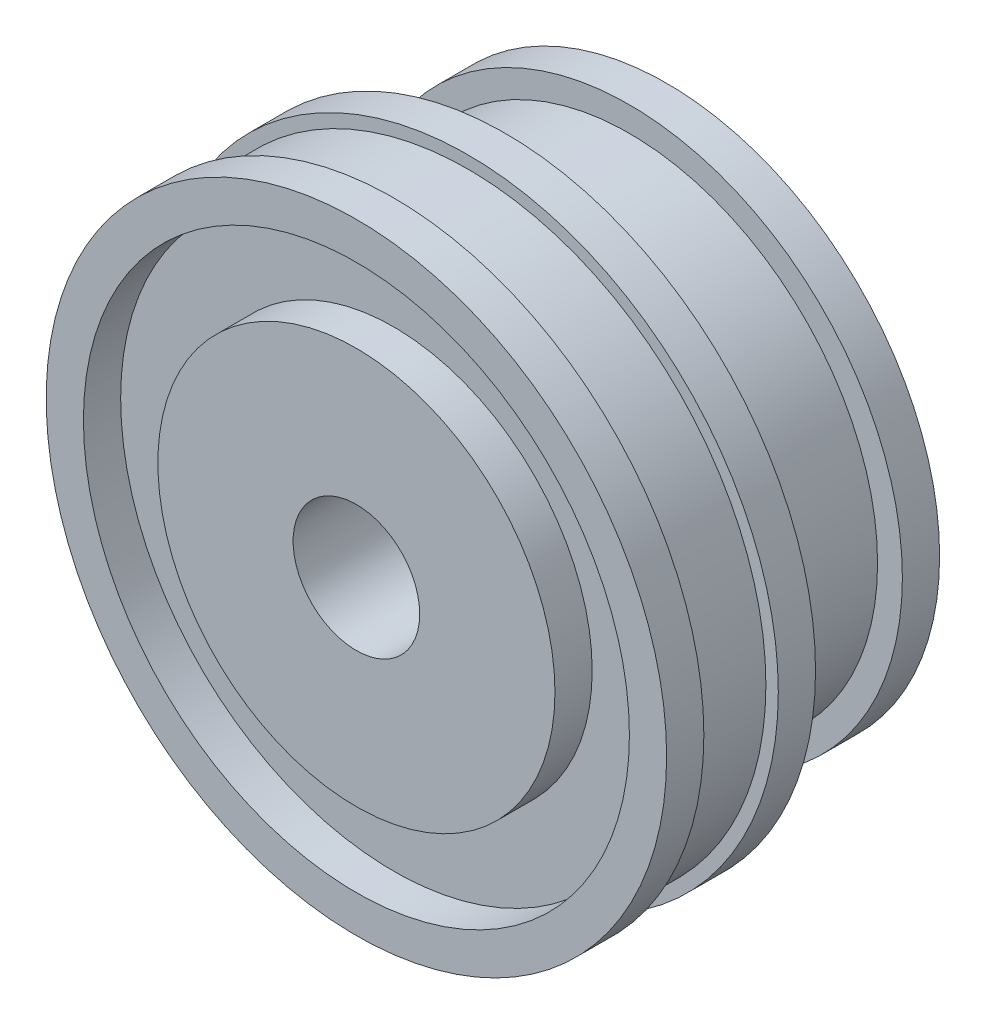
SolidWorks part; units mm, degrees
ref_plane "Front Plane" through (0, 0, 0) normal (0, 0, 1) x (1, 0, 0)
ref_plane "Top Plane" through (0, 0, 0) normal (0, 1, 0) x (1, 0, 0)
ref_plane "Right Plane" through (0, 0, 0) normal (1, 0, 0) x (0, 0, -1)
sketch "Sketch1" plane through (0, 0, 0) normal (0, 0, 1) x (1, 0, 0)
  circle A0 centre (0, 0) radius 22
  dimension "D1" = 44
extrude "Boss-Extrude1" add sketch "Sketch1" along normal blind 3
sketch "Sketch2" plane through (0, 0, 3) normal (0, 0, 1) x (1, 0, 0)
  circle A0 centre (0, 0) radius 20
  dimension "D1" = 40
extrude "Boss-Extrude2" add sketch "Sketch2" along normal blind 10
sketch "Sketch3" plane through (0, 0, 13) normal (0, 0, 1) x (1, 0, 0)
  circle A0 centre (0, 0) radius 25
  dimension "D1" = 50
extrude "Boss-Extrude3" add sketch "Sketch3" along normal blind 3
sketch "Sketch4" plane through (0, 0, 16) normal (0, 0, 1) x (1, 0, 0)
  circle A0 centre (0, 0) radius 24
  dimension "D1" = 48
extrude "Boss-Extrude4" add sketch "Sketch4" along normal blind 6
sketch "Sketch5" plane through (0, 0, 22) normal (0, 0, 1) x (1, 0, 0)
  circle A0 centre (0, 0) radius 25
  dimension "D1" = 50
extrude "Boss-Extrude5" add sketch "Sketch5" along normal blind 3
sketch "Sketch6" plane through (0, 0, 25) normal (0, 0, 1) x (1, 0, 0)
  circle A0 centre (0, 0) radius 16
  circle A1 centre (0, 0) radius 22
  dimension "D1" = 44
  dimension "D2" = 32
extrude "Cut-Extrude1" cut sketch "Sketch6" against normal blind 3
ref_plane "Plane1" through (0, 0, 4) normal (0, 0, 1) x (1, 0, 0)
sketch "Sketch8" plane through (0, 0, 4) normal (0, 0, 1) x (1, 0, 0)
  circle A0 centre (0, 0) radius 7
  dimension "D1" = 14
extrude "Cut-Extrude2" cut sketch "Sketch8" along normal blind 2
hole_wizard "M12 Tapped Hole1" positions "Sketch10" profile "Sketch9" tap size "M12" standard "DIN"
sketch "Sketch10" plane through (0, 0, 25) normal (0, 0, 1) x (1, 0, 0)
  point P0 (0, 0)
sketch "Sketch9" plane through (0, 0, 25) normal (1, 0, 0) x (0, -1, 0)
  line L0 (0, 0) -> (0, 19)
  line L1 (0, 19) -> (5.1, 19)
  line L2 (5.1, 19) -> (5.1, 0)
  line L5 (5.1, 0) -> (0, 0)
  line L11 (0, -6.35) -> (0, 107.95) construction
  dimension "Thru Tap Drill Dia." = 10.2
  dimension "Thru Tap Drill Depth" = 19
cosmetic thread "Hole Thread1" parameters "D2"=12
